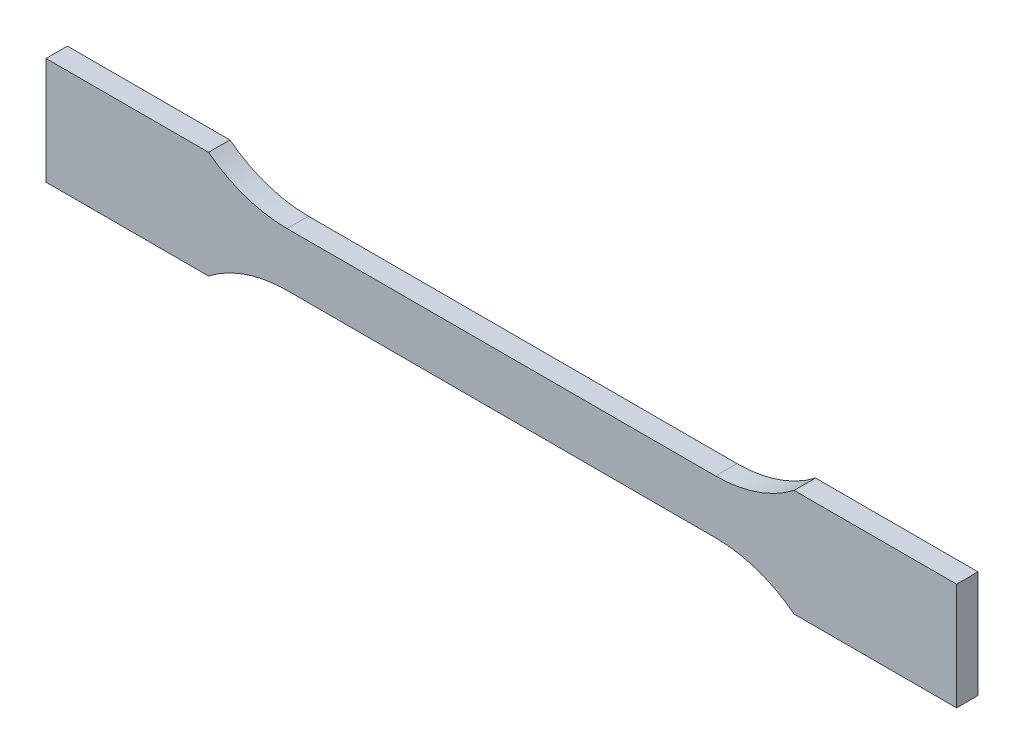
SolidWorks part; units mm, degrees
ref_plane "Front Plane" through (0, 0, 0) normal (0, 0, 1) x (1, 0, 0)
ref_plane "Top Plane" through (0, 0, 0) normal (0, 1, 0) x (1, 0, 0)
ref_plane "Right Plane" through (0, 0, 0) normal (1, 0, 0) x (0, 0, -1)
sketch "Sketch1" plane through (0, 0, 0) normal (0, 0, 1) x (1, 0, 0)
  line L0 (-85, 10) -> (-85, -10)
  line L1 (-85, -10) -> (-54.6629, -10)
  line L2 (-85, 10) -> (-54.6629, 10)
  line L3 (54.6629, 10) -> (85, 10)
  line L4 (85, 10) -> (85, -10)
  line L5 (85, -10) -> (54.6629, -10)
  line L6 (-40, -5) -> (40, -5)
  line L7 (-40, 5) -> (40, 5)
  line L11 (0, -44.7868) -> (0, 44.7868) construction
  line L12 (-57.5, 19.8545) -> (-57.5, -21.6) construction
  line L13 (57.5, 19.8545) -> (57.5, -21.6) construction
  line L14 (-25, 13.3091) -> (-25, -10) construction
  line L15 (25, 13.3091) -> (25, -10) construction
  line L17 (55, 0) -> (-55, 0) construction
  arc A1 (40, 5) -> (54.6629, 10) centre (40, 29) ccw
  arc A2 (40, -5) -> (54.6629, -10) centre (40, -29) cw
  arc A3 (-40, -5) -> (-54.6629, -10) centre (-40, -29) ccw
  arc A4 (-40, 5) -> (-54.6629, 10) centre (-40, 29) cw
  point P28 (0, 0)
  point P29 (0, 0)
  dimension "D7" = 24
  dimension "D1" = 20
  dimension "D3" = 10
  dimension "D5" = 80
  dimension "D6" = 40
  dimension "D8" = 170
  dimension "D9" = 115
  dimension "D10" = 57.5
  dimension "D11" = 50
  dimension "D12" = 25
  dimension "D2" = 5
  dimension "D4" = 10
extrude "Boss-Extrude1" add sketch "Sketch1" along normal mid plane 4
equation "\"b2\"=20"
equation "\"D1@Sketch1\"=\"b2\""
equation "\"b1\"=10"
equation "\"D3@Sketch1\"=\"b1\""
equation "\"l1\"=80"
equation "\"D5@Sketch1\"=\"l1\""
equation "\"D6@Sketch1\"=\"l1\"/2"
equation "\"R\"=24"
equation "\"D7@Sketch1\"=\"R\""
equation "\"L\"=115"
equation "\"D9@Sketch1\"=\"L\""
equation "\"D10@Sketch1\"=\"L\"/2"
equation "\"L0\"=50"
equation "\"D11@Sketch1\"=\"L0\""
equation "\"D12@Sketch1\"=\"L0\"/2"
equation "\"h\"=4"
equation "\"D1@Boss-Extrude1\"=\"h\""
equation "\"D2@Sketch1\"=\"b1\"/2"
equation "\"D4@Sketch1\"=\"b2\"/2"
